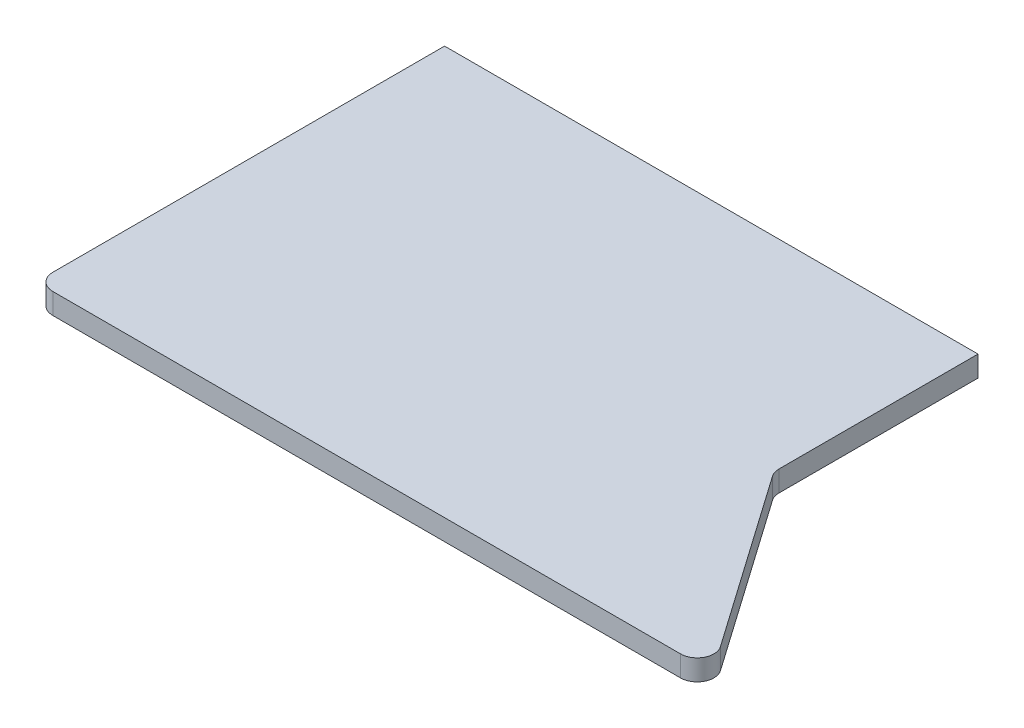
SolidWorks part; units mm, degrees
material "Plain Carbon Steel"
ref_plane "Front Plane" through (0, 0, 0) normal (0, 0, 1) x (1, 0, 0)
ref_plane "Top Plane" through (0, 0, 0) normal (0, 1, 0) x (1, 0, 0)
ref_plane "Right Plane" through (0, 0, 0) normal (1, 0, 0) x (0, 0, -1)
sketch "Sketch1" plane through (0, 0, 0) normal (0, 1, 0) x (1, 0, 0)
  line L0 (81.28, 31.115) -> (103.067, 0)
  line L1 (0, 0) -> (81.28, 0)
  line L2 (0, 0) -> (0, 62.23)
  line L3 (0, 62.23) -> (81.28, 62.23)
  line L4 (81.28, 0) -> (81.28, 62.23)
  line L5 (103.067, 0) -> (81.28, 0)
  dimension "D1" = 81.28
  dimension "D2" = 62.23
  dimension "D3" = 35
extrude "Boss-Extrude1" add sketch "Sketch1" along normal blind 3.175 contours L5 L0 L4 | L1 L4 L3 L2
fillet "Fillet1" radius 2.54 3 edges at (0, 1.5875, 0) (81.28, 1.5875, -31.115) (103.067, 1.5875, 0)
